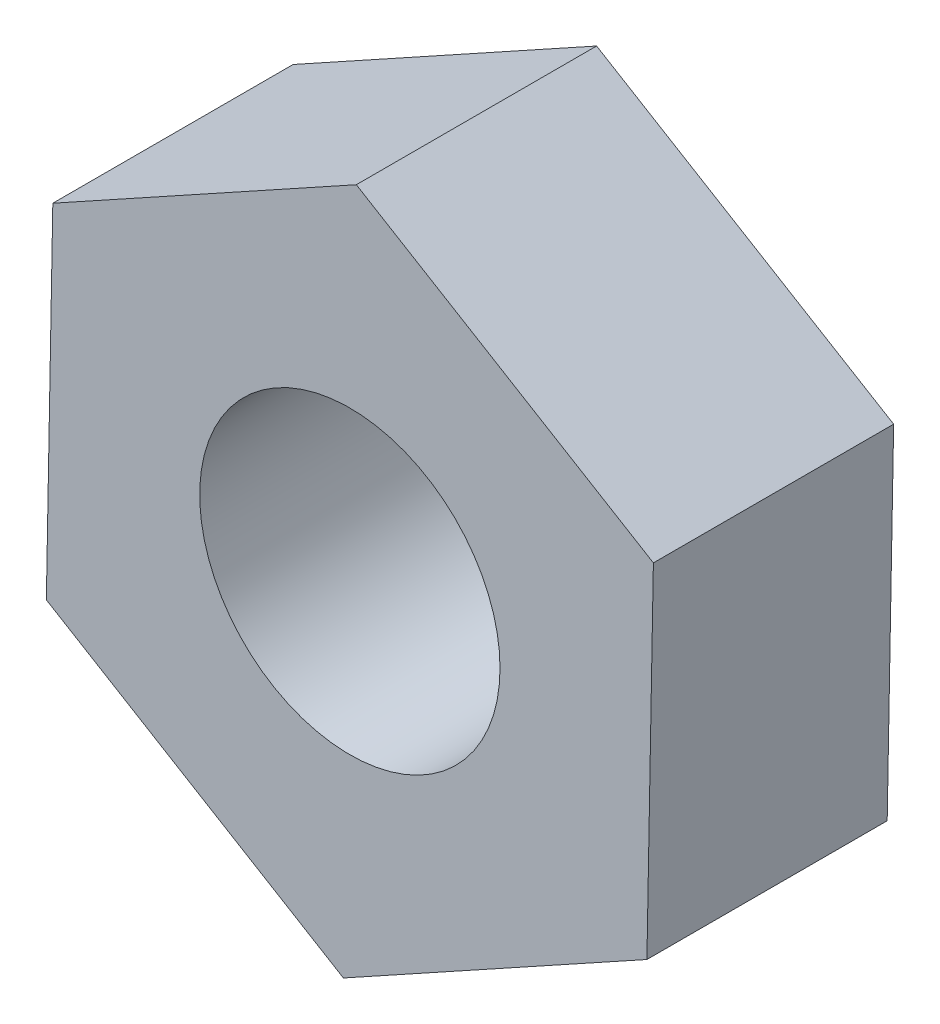
SolidWorks part; units mm, degrees
ref_plane "前视基准面" through (0, 0, 0) normal (0, 0, 1) x (1, 0, 0)
ref_plane "上视基准面" through (0, 0, 0) normal (0, 1, 0) x (1, 0, 0)
ref_plane "右视基准面" through (0, 0, 0) normal (1, 0, 0) x (0, 0, -1)
sketch "草图1" plane through (0, 0, 0) normal (0, 0, 1) x (1, 0, 0)
  line L1 (-1.9781, 1.1918) -> (-2.0212, -1.1172)
  line L2 (-2.0212, -1.1172) -> (-0.0431, -2.309)
  line L3 (-0.0431, -2.309) -> (1.9781, -1.1918)
  line L4 (1.9781, -1.1918) -> (2.0212, 1.1172)
  line L5 (2.0212, 1.1172) -> (0.0431, 2.309)
  line L6 (0.0431, 2.309) -> (-1.9781, 1.1918)
  circle A0 centre (0, 0) radius 1
  circle A1 centre (0, 0) radius 2 construction
  dimension "D1" = 1
  dimension "D2" = 4
extrude "凸台-拉伸1" add sketch "草图1" along normal blind 1.6
cosmetic thread "装饰螺纹线1"
